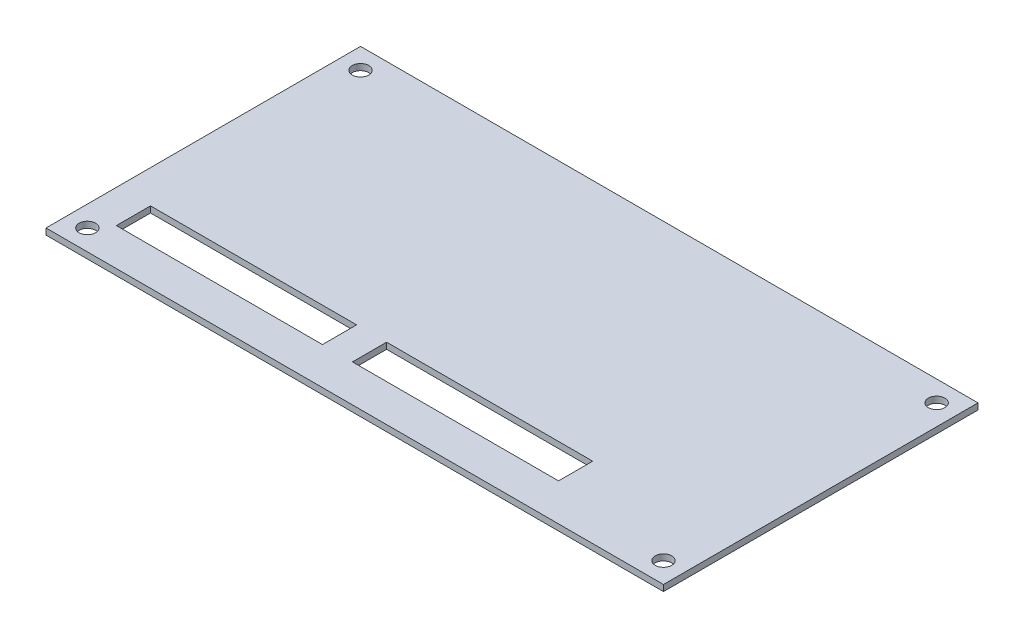
SolidWorks part; units mm, degrees
ref_plane "Front Plane" through (0, 0, 0) normal (0, 0, 1) x (1, 0, 0)
ref_plane "Top Plane" through (0, 0, 0) normal (0, 1, 0) x (1, 0, 0)
ref_plane "Right Plane" through (0, 0, 0) normal (1, 0, 0) x (0, 0, -1)
sketch "Sketch1" plane through (0, 0, 0) normal (0, 1, 0) x (1, 0, 0)
  line L1 (-74.6, -38) -> (74.6, -38)
  line L2 (-74.6, -38) -> (-74.6, 38)
  line L3 (-74.6, 38) -> (74.6, 38)
  line L4 (74.6, -38) -> (74.6, 38)
  line L5 (-74.6, -38) -> (74.6, 38) construction
  line L6 (-74.6, 38) -> (74.6, -38) construction
  line L7 (-66.6, -29) -> (-16.8, -29)
  line L8 (-66.6, -29) -> (-66.6, -20.75)
  line L9 (-66.6, -20.75) -> (-16.8, -20.75)
  line L10 (-16.8, -29) -> (-16.8, -20.75)
  line L11 (-66.6, -29) -> (-16.8, -20.75) construction
  line L12 (-66.6, -20.75) -> (-16.8, -29) construction
  line L13 (-9.55, -29) -> (40.25, -29)
  line L14 (-9.55, -29) -> (-9.55, -20.75)
  line L15 (-9.55, -20.75) -> (40.25, -20.75)
  line L16 (40.25, -29) -> (40.25, -20.75)
  line L17 (-9.55, -29) -> (40.25, -20.75) construction
  line L18 (-9.55, -20.75) -> (40.25, -29) construction
  circle A0 centre (-69.6, 33) radius 2
  circle A1 centre (69.6, 33) radius 2
  circle A2 centre (69.6, -33) radius 2
  circle A3 centre (-69.6, -33) radius 2
  point P0 (0, 0)
  point P14 (-41.7, -24.875)
  point P19 (15.35, -24.875)
  point P24 (27.5541, -28.2788)
  point P25 (-12.475, -23.7117)
  point P26 (-43.0117, -28.2788)
  point P27 (-27.609, -29.3534)
  dimension "D3" = 4
  dimension "D1" = 76
  dimension "D2" = 149.2
  dimension "D4" = 5
  dimension "D5" = 5
  dimension "D6" = 5
  dimension "D7" = 5
  dimension "D8" = 8.25
  dimension "D9" = 49.8
  dimension "D10" = 7.25
  dimension "D11" = 8
  dimension "D12" = 9
extrude "Boss-Extrude1" add sketch "Sketch1" against normal blind 1.5
